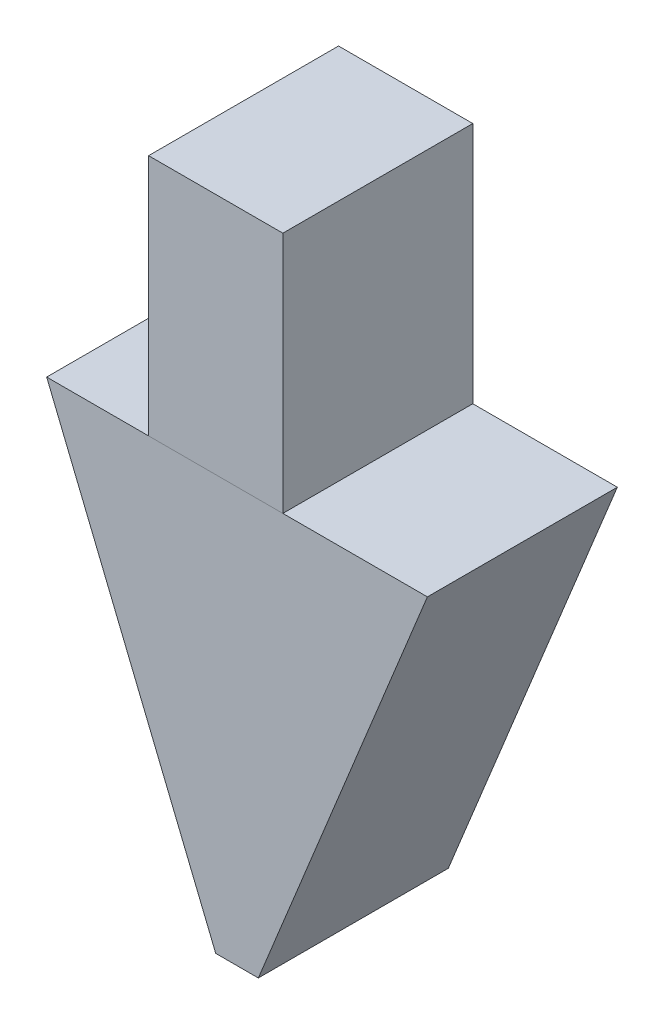
SolidWorks part; units mm, degrees
ref_plane "Front Plane" through (0, 0, 0) normal (0, 0, 1) x (1, 0, 0)
ref_plane "Top Plane" through (0, 0, 0) normal (0, 1, 0) x (1, 0, 0)
ref_plane "Right Plane" through (0, 0, 0) normal (1, 0, 0) x (0, 0, -1)
sketch "Sketch1" plane through (0, 0, 0) normal (0, 0, 1) x (1, 0, 0)
  line L0 (-44.8748, 0) -> (44.8748, 0)
  line L1 (44.8748, 0) -> (400.887, 873.1481)
  line L7 (-400.887, 873.1481) -> (400.887, 873.1481)
  line L8 (-44.8748, 0) -> (-400.887, 873.1481)
extrude "Boss-Extrude1" add sketch "Sketch1" along normal mid plane 400
sketch "Sketch2" plane through (0, 0, 0) normal (0, 0, 1) x (1, 0, 0)
  line L0 (-186.2436, 873.1481) -> (96.4939, 873.1481)
  line L3 (96.4939, 873.1481) -> (96.4939, 1384.2505)
  line L4 (96.4939, 1384.2505) -> (-186.2436, 1384.2505)
  line L5 (-186.2436, 873.1481) -> (-186.2436, 1384.2505)
extrude "Boss-Extrude2" add sketch "Sketch2" along normal mid plane 400 separate body
